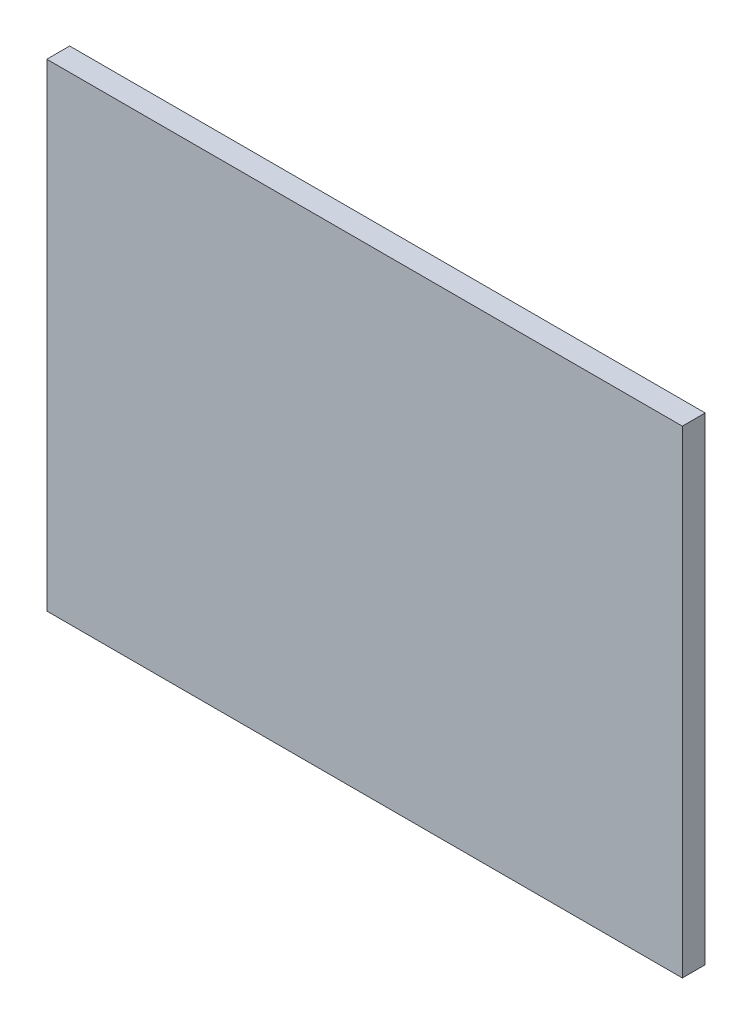
SolidWorks part; units mm, degrees
ref_plane "Front Plane" through (0, 0, 0) normal (0, 0, 1) x (1, 0, 0)
ref_plane "Top Plane" through (0, 0, 0) normal (0, 1, 0) x (1, 0, 0)
ref_plane "Right Plane" through (0, 0, 0) normal (1, 0, 0) x (0, 0, -1)
sketch "Sketch1" plane through (0, 0, 0) normal (0, 0, 1) x (1, 0, 0)
  line L1 (0, 0) -> (500, 0)
  line L2 (0, 0) -> (0, 376)
  line L3 (0, 376) -> (500, 376)
  line L4 (500, 0) -> (500, 376)
  dimension "D1" = 500
  dimension "D2" = 376
extrude "Boss-Extrude1" add sketch "Sketch1" along normal blind 18
